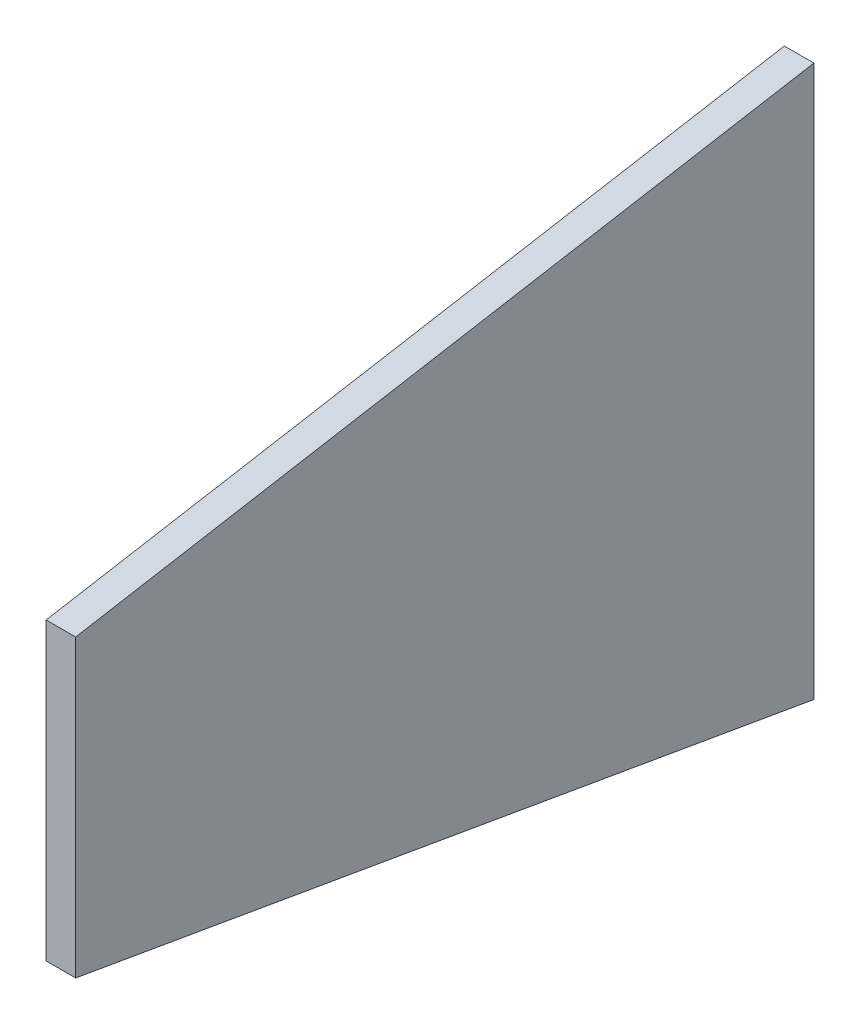
SolidWorks part; units mm, degrees
material "Balsa"
ref_plane "Front Plane" through (0, 0, 0) normal (1, 0, 0) x (0, 1, 0)
ref_plane "Top Plane" through (0, 0, 0) normal (0, 0, 1) x (0, 1, 0)
ref_plane "Right Plane" through (0, 0, 0) normal (0, 1, 0) x (-1, 0, 0)
sketch "Sketch1" plane through (0, 0, 0) normal (1, 0, 0) x (0, 1, 0)
  line L0 (0, 0) -> (56, 0)
  line L1 (56, 0) -> (43, 75)
  line L2 (43, 75) -> (13, 75)
  line L3 (13, 75) -> (0, 0)
  point P3 (28, 0)
  point P6 (28, 75)
  dimension "D1" = 56
  dimension "D2" = 30
  dimension "D3" = 75
extrude "Boss-Extrude1" add sketch "Sketch1" along normal blind 3
